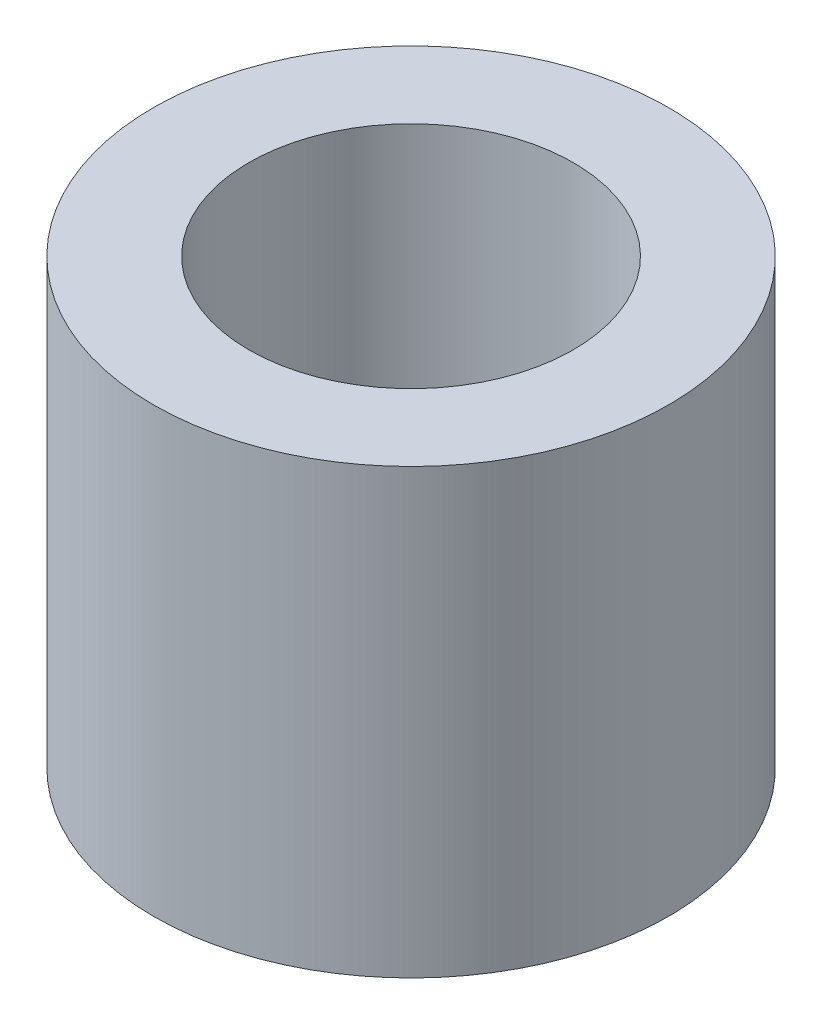
SolidWorks part; units mm, degrees
ref_plane "Front" through (0, 0, 0) normal (0, 0, 1) x (1, 0, 0)
ref_plane "Top" through (0, 0, 0) normal (0, 1, 0) x (1, 0, 0)
ref_plane "Right" through (0, 0, 0) normal (1, 0, 0) x (0, 0, -1)
sketch "Sketch2" plane through (0, 0, 0) normal (0, 1, 0) x (1, 0, 0)
  circle A1 centre (0, 0) radius 4
  circle A2 centre (0, 0) radius 6.35
  dimension "D1" = 8
  dimension "D2" = 12.7
extrude "Boss-Extrude1" add sketch "Sketch2" along normal blind 10.922
